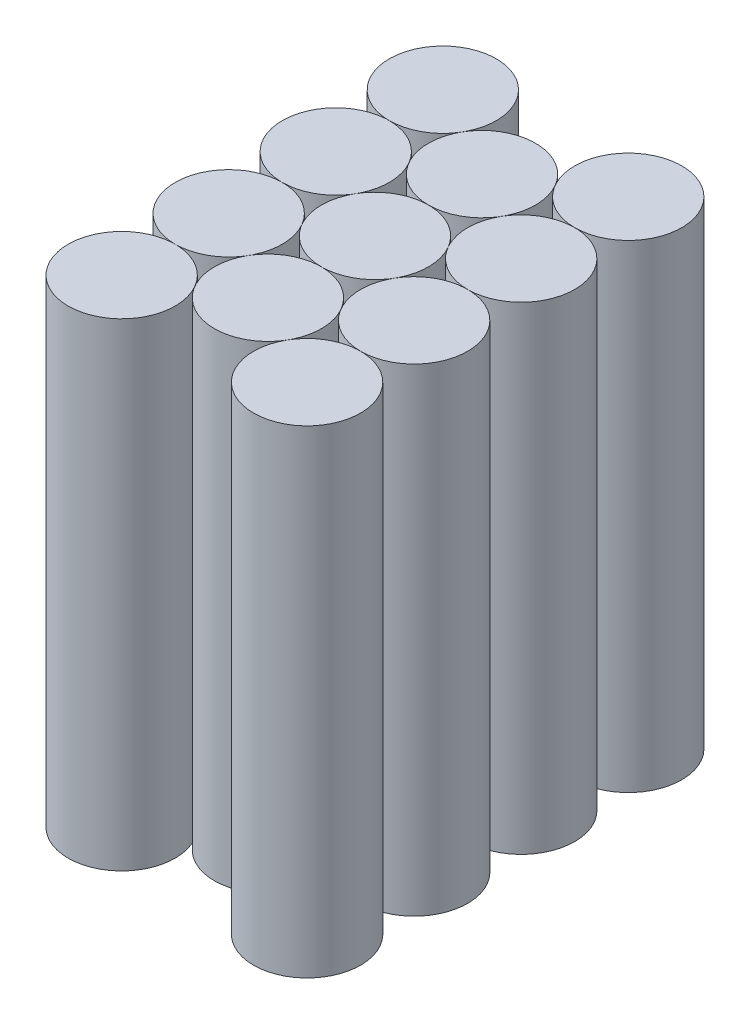
SolidWorks part; units mm, degrees
ref_plane "Front Plane" through (0, 0, 0) normal (0, 0, 1) x (1, 0, 0)
ref_plane "Top Plane" through (0, 0, 0) normal (0, 1, 0) x (1, 0, 0)
ref_plane "Right Plane" through (0, 0, 0) normal (1, 0, 0) x (0, 0, -1)
sketch "Sketch1" plane through (0, 0, 0) normal (0, 1, 0) x (1, 0, 0)
  line L0 (0, 0) -> (0, 83.4828) construction
  line L1 (-12.9904, -6.5589) -> (-12.9904, 106.0355) construction
  line L2 (12.9904, -6.5589) -> (12.9904, 106.0355) construction
  circle A0 centre (0, 0) radius 7.5 construction
  circle A1 centre (0, 30) radius 7.5
  circle A2 centre (0, 45) radius 7.5
  circle A3 centre (0, 15) radius 7.5
  circle A8 centre (-12.9904, 7.5) radius 7.5
  circle A9 centre (-12.9904, 22.5) radius 7.5
  circle A10 centre (-12.9904, 37.5) radius 7.5
  circle A11 centre (-12.9904, 52.5) radius 7.5
  circle A12 centre (12.9904, 7.5) radius 7.5
  circle A13 centre (12.9904, 22.5) radius 7.5
  circle A14 centre (12.9904, 37.5) radius 7.5
  circle A15 centre (12.9904, 52.5) radius 7.5
  dimension "D1" = 15
extrude "Boss-Extrude1" add sketch "Sketch1" along normal blind 67 contours A12 | A0 | A3 | A8 | A9 | A10 | A11 | A2 | A1 | A15 | A14 | A13 A3
sketch "Sketch3" plane through (0, 0, 0) normal (0, 1, 0) x (1, 0, 0)
  line L1 (-20.4904, 60) -> (20.4904, 60)
  line L6 (-20.4904, 60) -> (-20.4904, 0)
  line L11 (-20.4904, 0) -> (20.4904, 0)
  line L12 (20.4904, 60) -> (20.4904, 0)
  circle A0 centre (12.9904, 7.5) radius 7.5 construction
  circle A3 centre (12.9904, 22.5) radius 7.5 construction
  circle A7 centre (-12.9904, 52.5) radius 7.5 construction
